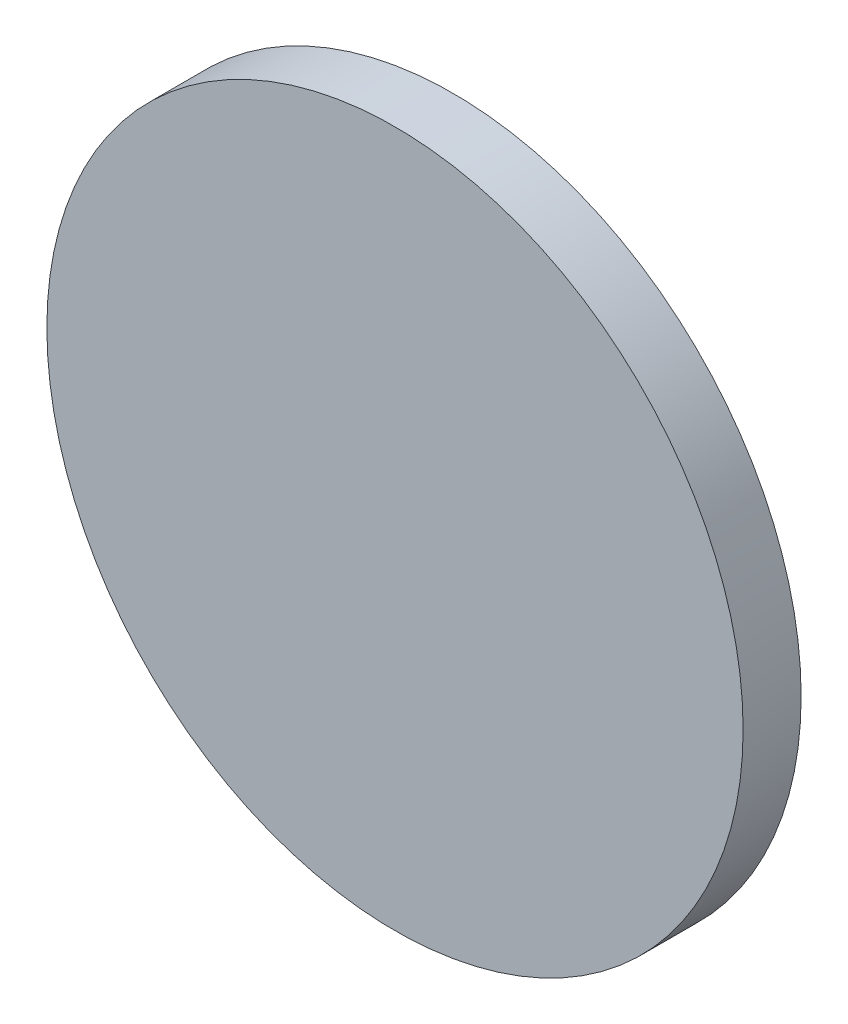
SolidWorks part; units mm, degrees
material "Acrylic (Medium-high impact)"
ref_plane "Front Plane" through (0, 0, 0) normal (0, 0, 1) x (1, 0, 0)
ref_plane "Top Plane" through (0, 0, 0) normal (0, 1, 0) x (1, 0, 0)
ref_plane "Right Plane" through (0, 0, 0) normal (1, 0, 0) x (0, 0, -1)
sketch "Sketch2" plane through (0, 0, 0) normal (0, 0, 1) x (1, 0, 0)
  circle A0 centre (0, 0) radius 76.2
  dimension "D1" = 152.4
extrude "Boss-Extrude1" add sketch "Sketch2" along normal blind 12.7
